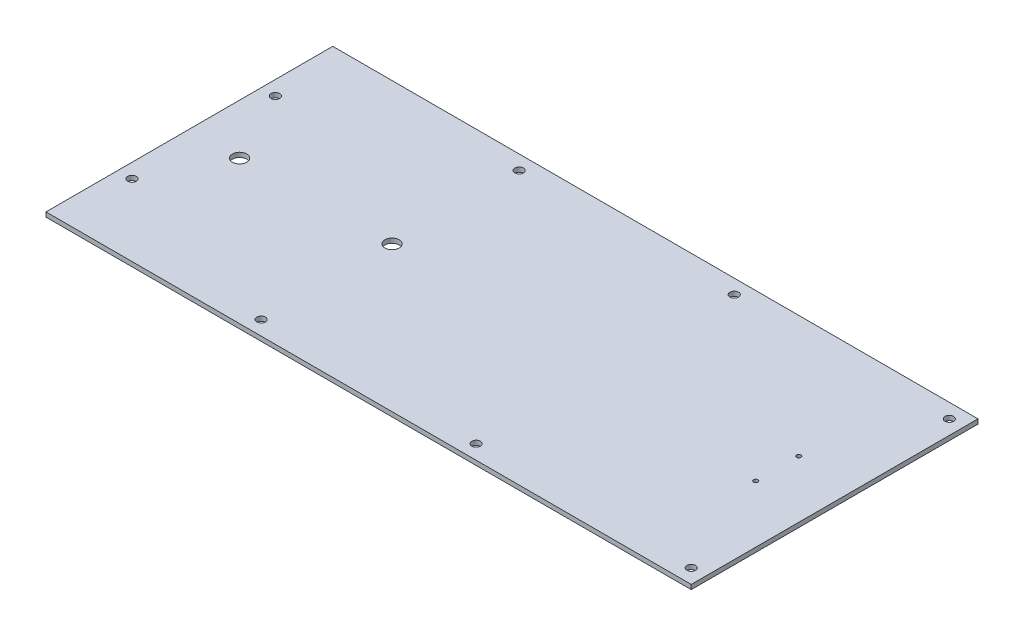
SolidWorks part; units mm, degrees
ref_plane "Front Plane" through (0, 0, 0) normal (0, 0, 1) x (1, 0, 0)
ref_plane "Top Plane" through (0, 0, 0) normal (0, 1, 0) x (1, 0, 0)
ref_plane "Right Plane" through (0, 0, 0) normal (1, 0, 0) x (0, 0, -1)
sketch "Sketch1" plane through (0, 0, 0) normal (0, 1, 0) x (1, 0, 0)
  line L1 (70, 110.4681) -> (450, 110.4681)
  line L3 (70, 310.4681) -> (450, 310.4681)
  line L4 (450, 110.4681) -> (450, 310.4681)
  line L13 (0, 310.4681) -> (0, 110.4681)
  line L16 (70, 110.4681) -> (0, 110.4681)
  line L17 (0, 310.4681) -> (70, 310.4681)
  circle A4 centre (410, 225.4681) radius 1.5
  circle A5 centre (410, 195.4681) radius 1.5
  circle A7 centre (10, 260.4681) radius 3
  circle A9 centre (440, 300.4681) radius 3
  circle A10 centre (140, 300.4681) radius 3
  circle A12 centre (290, 300.4681) radius 3
  circle A15 centre (440, 120.4681) radius 3
  circle A16 centre (290, 120.4681) radius 3
  circle A18 centre (140, 120.4681) radius 3
  circle A20 centre (10, 160.4681) radius 3
  circle A21 centre (35, 210.4681) radius 5
  circle A22 centre (140, 211.8084) radius 5
  dimension "D10" = 3
  dimension "D17" = 10
  dimension "D20" = 150
  dimension "D26" = 6
  dimension "D28" = 6
  dimension "D30" = 6
  dimension "D31" = 6
  dimension "D4" = 35
  dimension "D5" = 200
  dimension "D11" = 40
  dimension "D12" = 40
  dimension "D18" = 10
extrude "Boss-Extrude1" add sketch "Sketch1" along normal blind 3.175
